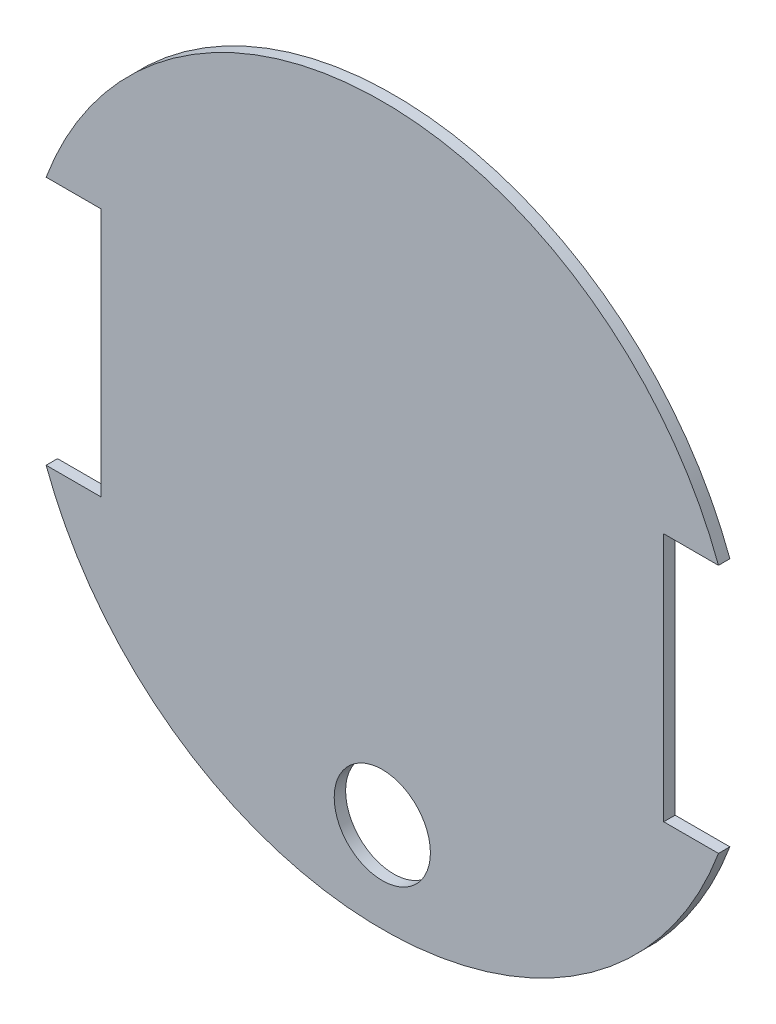
SolidWorks part; units mm, degrees
ref_plane "Přední rovina" through (0, 0, 0) normal (0, 0, 1) x (1, 0, 0)
ref_plane "Horní rovina" through (0, 0, 0) normal (0, 1, 0) x (1, 0, 0)
ref_plane "Pravá rovina" through (0, 0, 0) normal (1, 0, 0) x (0, 0, -1)
sketch "Skica1" plane through (0, 0, 0) normal (0, 0, 1) x (1, 0, 0)
  line L0 (0, 47.15) -> (0, -47.15) construction
  line L1 (-47.1239, 0) -> (47.1239, 0) construction
  line L2 (-44.2059, 16.4) -> (-37.0059, 16.4)
  line L3 (44.2059, 16.4) -> (37.0059, 16.4)
  line L4 (-37.0059, 16.4) -> (-37.0059, 0)
  line L5 (37.0059, 16.4) -> (37.0059, -16.4)
  line L6 (-37.0059, -16.4) -> (-44.2059, -16.4)
  line L7 (37.0059, -16.4) -> (44.2059, -16.4)
  line L8 (-37.0059, 0) -> (-37.0059, -16.4)
  arc A0 (-44.2059, -16.4) -> (44.2059, -16.4) centre (0, 0) ccw
  arc A1 (44.2059, 16.4) -> (-44.2059, 16.4) centre (0, 0) ccw
  dimension "D1" = 94.3
  dimension "D2" = 7.2
  dimension "D3" = 16.4
  dimension "D4" = 16.4
  dimension "D5" = 7.2
  dimension "D6" = 74.0118
extrude "Přidat vysunutím4" add sketch "Skica1" along normal blind 1.5
sketch "Skica14" plane through (0, 0, 0) normal (0, 0, -1) x (-1, 0, 0)
  line L0 (-37.0059, -13.15) -> (37.0059, -13.15) construction
  line L3 (-37.0059, -16.4) -> (-37.0059, 16.4) construction
  line L4 (37.0059, 16.4) -> (37.0059, -16.4) construction
  arc A0 (-44.2059, -16.4) -> (44.2059, -16.4) centre (0, 0) ccw construction
  text T0 "3π" font "Lucida Calligraphy" height 3.5
  text T1 "Pololu"
  point P11 (0, -47.15)
  dimension "D1" = 34
extrude "Přidat vysunutím14" add sketch "Skica14" along normal blind 0.01
sketch "Skica15" plane through (0, 0, 0) normal (0, 0, -1) x (-1, 0, 0)
  line L0 (0, 0) -> (0, -47.15) construction
  arc A0 (-44.2059, -16.4) -> (44.2059, -16.4) centre (0, 0) ccw construction
  circle A1 centre (0, -35.275) radius 6.325
  dimension "D1" = 12.65
  dimension "D2" = 5.55
extrude "Odebrat vysunutím1" cut sketch "Skica15" against normal up to surface (1.5 mm away) up to face at (0, 0, 1.5)
